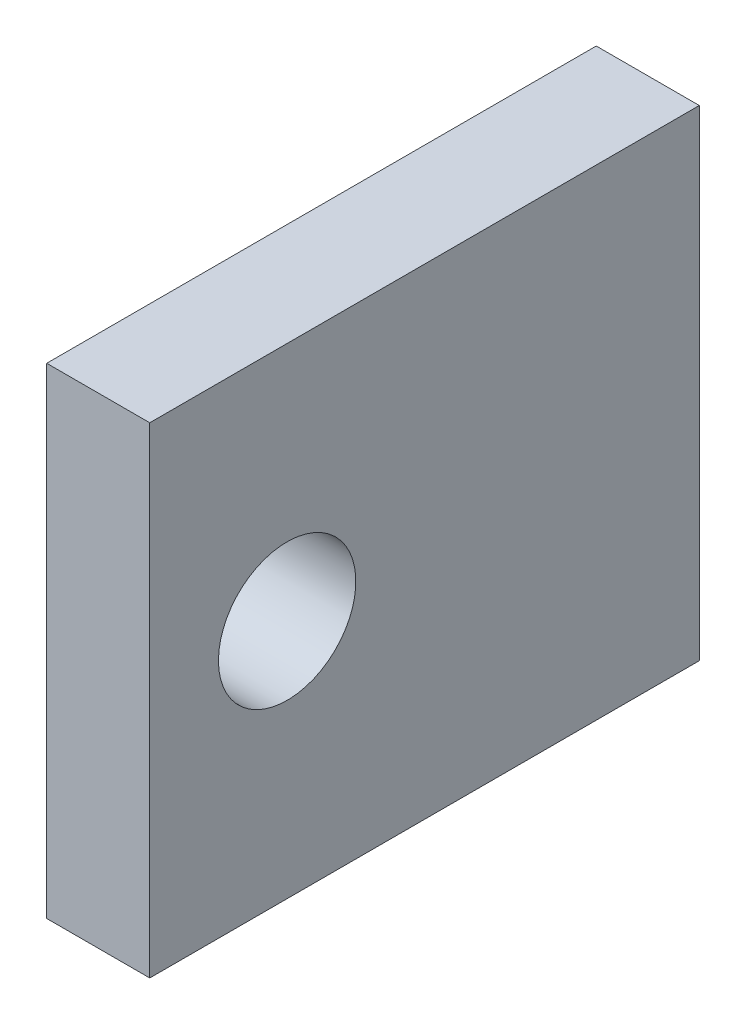
SolidWorks part; units mm, degrees
ref_plane "Front Plane" through (0, 0, 0) normal (0, 0, 1) x (1, 0, 0)
ref_plane "Top Plane" through (0, 0, 0) normal (0, 1, 0) x (1, 0, 0)
ref_plane "Right Plane" through (0, 0, 0) normal (1, 0, 0) x (0, 0, -1)
sketch "Sketch1" plane through (0, 0, 0) normal (1, 0, 0) x (0, 0, -1)
  line L1 (-25.4, -22.225) -> (25.4, -22.225)
  line L2 (-25.4, -22.225) -> (-25.4, 22.225)
  line L3 (-25.4, 22.225) -> (25.4, 22.225)
  line L4 (25.4, -22.225) -> (25.4, 22.225)
  line L5 (-25.4, -22.225) -> (25.4, 22.225) construction
  line L6 (-25.4, 22.225) -> (25.4, -22.225) construction
  circle A0 centre (-12.7, 0) radius 6.35
  point P0 (0, 0)
  dimension "D2" = 12.7
  dimension "D3" = 38.1
  dimension "D1" = 50.8
  dimension "D4" = 44.45
extrude "Boss-Extrude1" add sketch "Sketch1" along normal blind 9.525
